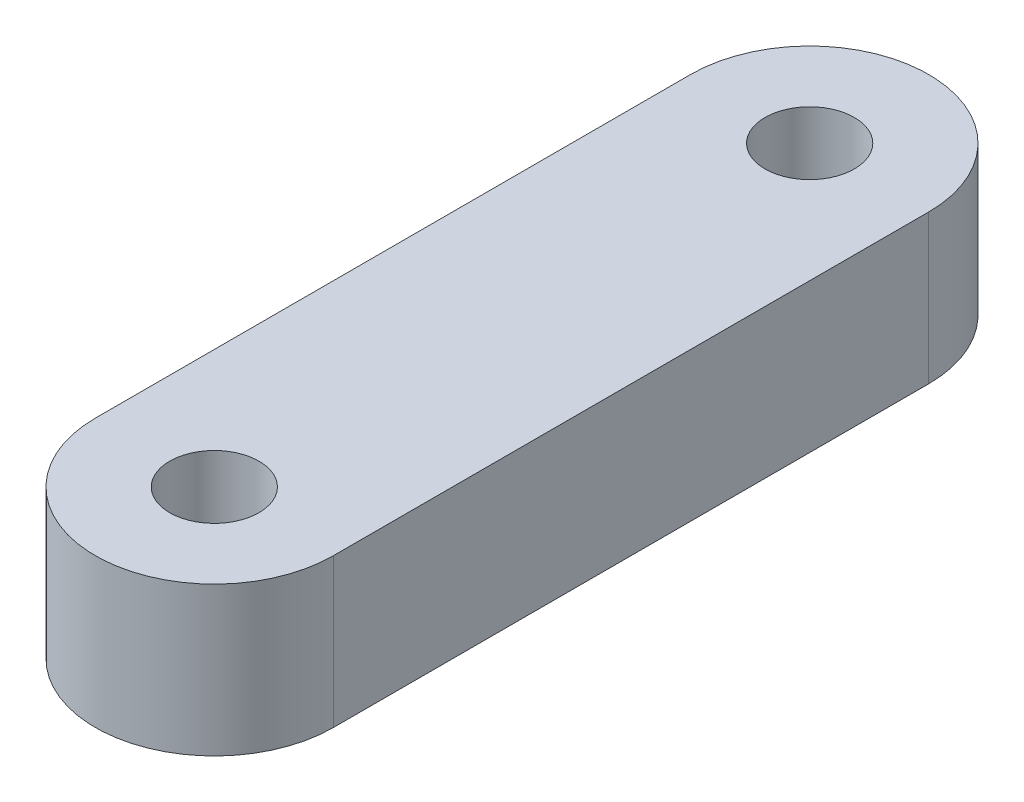
SolidWorks part; units mm, degrees
ref_plane "前视基准面" through (0, 0, 0) normal (0, 0, 1) x (1, 0, 0)
ref_plane "上视基准面" through (0, 0, 0) normal (0, 1, 0) x (1, 0, 0)
ref_plane "右视基准面" through (0, 0, 0) normal (1, 0, 0) x (0, 0, -1)
sketch "草图1" plane through (0, 0, 0) normal (0, 1, 0) x (1, 0, 0)
  line L0 (0, 0) -> (0, 10)
  line L1 (0, 0) -> (0, -10)
  line L2 (0, 10) -> (0, -10) construction
  line L3 (4, 10) -> (4, -10)
  line L4 (-4, 10) -> (-4, -10)
  circle A0 centre (0, 10) radius 1.5
  circle A1 centre (0, -10) radius 1.5
  arc A2 (4, 10) -> (-4, 10) centre (0, 10) ccw
  arc A3 (-4, -10) -> (4, -10) centre (0, -10) ccw
  point P6 (0, 0)
extrude "凸台-拉伸1" add sketch "草图1" along normal blind 5
